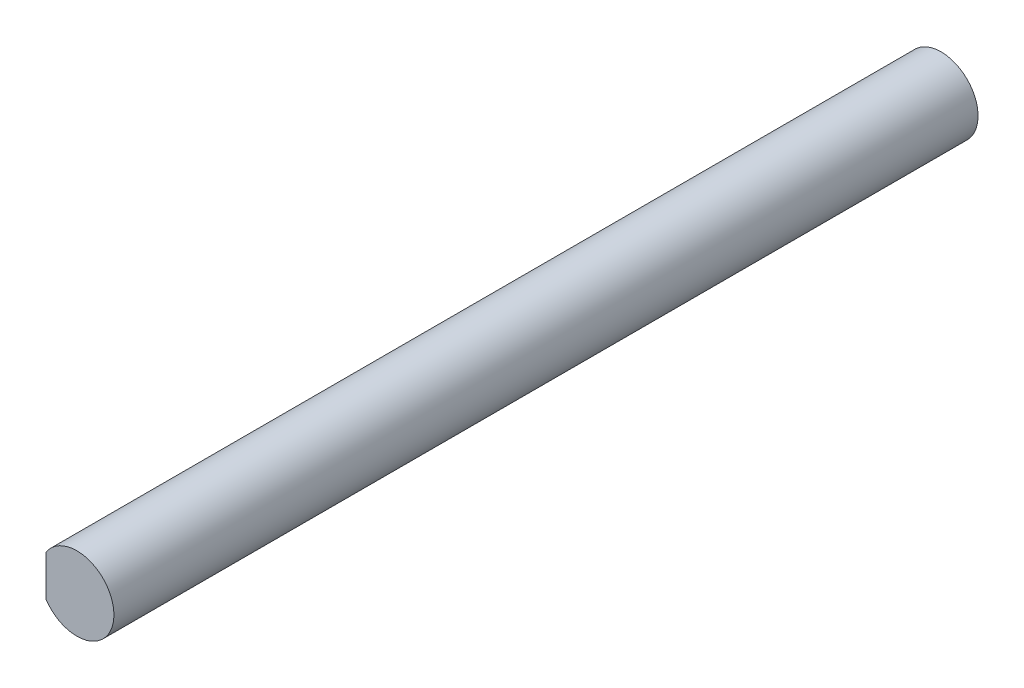
SolidWorks part; units mm, degrees
ref_plane "Front Plane" through (0, 0, 0) normal (0, 0, 1) x (1, 0, 0)
ref_plane "Top Plane" through (0, 0, 0) normal (0, 1, 0) x (1, 0, 0)
ref_plane "Right Plane" through (0, 0, 0) normal (1, 0, 0) x (0, 0, -1)
sketch "Sketch1" plane through (0, 0, 0) normal (0, 0, 1) x (1, 0, 0)
  line L0 (-2.5, 1.6583) -> (-2.5, -1.6583)
  line L1 (3, -3.1656) -> (3, 4.1153) construction
  arc A0 (-2.5, -1.6583) -> (-2.5, 1.6583) centre (0, 0) ccw
  dimension "D1" = 6
  dimension "D2" = 5.5
extrude "Boss-Extrude1" add sketch "Sketch1" along normal blind 70
